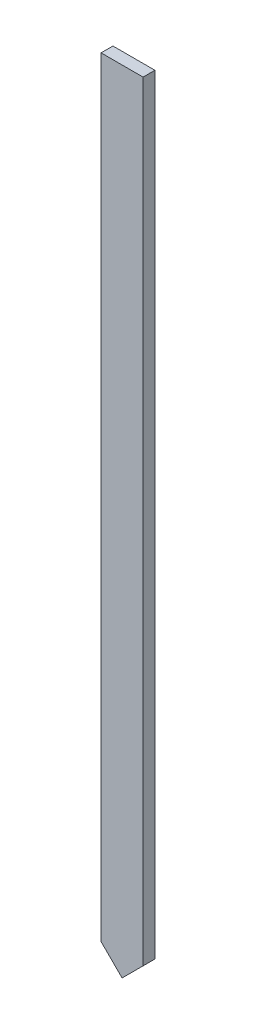
SolidWorks part; units mm, degrees
ref_plane "Front Plane" through (0, 0, 0) normal (0, 0, 1) x (1, 0, 0)
ref_plane "Top Plane" through (0, 0, 0) normal (0, 1, 0) x (1, 0, 0)
ref_plane "Right Plane" through (0, 0, 0) normal (1, 0, 0) x (0, 0, -1)
sketch "Sketch1" plane through (0, 0, 0) normal (0, 0, 1) x (1, 0, 0)
  line L0 (-3.1298, -22.587) -> (0.4152, -19.042)
  line L1 (0.4152, 110.913) -> (-6.6748, 110.913)
  line L7 (-3.1298, -22.587) -> (-6.6748, -19.042)
  line L8 (0.4152, -19.042) -> (0.4152, 110.913)
  line L9 (-6.6748, -19.042) -> (-6.6748, 110.913)
  point P0 (-3.1298, 44.163)
extrude "Boss-Extrude1" add sketch "Sketch1" along normal blind 2
